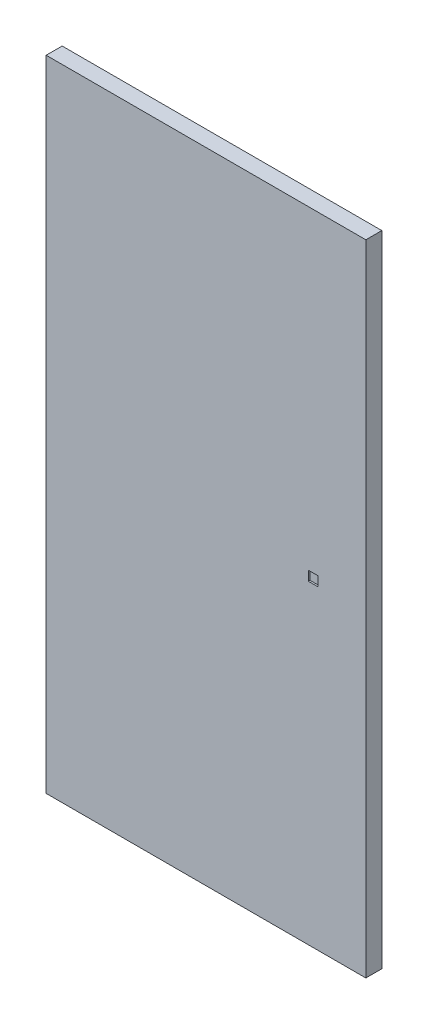
SolidWorks part; units mm, degrees
ref_plane "Front Plane" through (0, 0, 0) normal (0, 0, 1) x (1, 0, 0)
ref_plane "Top Plane" through (0, 0, 0) normal (0, 1, 0) x (1, 0, 0)
ref_plane "Right Plane" through (0, 0, 0) normal (1, 0, 0) x (0, 0, -1)
sketch "Sketch1" plane through (0, 0, 0) normal (0, 0, 1) x (1, 0, 0)
  line L1 (500, -1000) -> (-500, -1000)
  line L2 (500, -1000) -> (500, 1000)
  line L3 (500, 1000) -> (-500, 1000)
  line L4 (-500, -1000) -> (-500, 1000)
  line L5 (500, -1000) -> (-500, 1000) construction
  line L6 (500, 1000) -> (-500, -1000) construction
  point P0 (0, 0)
  dimension "D1" = 2000
  dimension "D2" = 1000
extrude "Boss-Extrude1" add sketch "Sketch1" along normal blind 50
sketch "Sketch2" plane through (0, 0, 50) normal (0, 0, 1) x (1, 0, 0)
  line L0 (500, 15) -> (-500, 15)
  line L1 (500, -1000) -> (500, 1000) construction
  line L2 (-500, 1000) -> (-500, -1000) construction
  line L3 (-934.7939, 0) -> (704.2445, 0) construction
  line L4 (-500, -15) -> (500, -15)
  line L5 (350, 1000) -> (350, -1000) construction
  line L6 (500, 1000) -> (-500, 1000) construction
  line L7 (-500, -1000) -> (500, -1000) construction
  line L9 (350, 15) -> (320, 15)
  line L10 (350, 15) -> (350, -15)
  line L11 (350, -15) -> (320, -15)
  line L12 (320, 15) -> (320, -15)
  line L13 (350, 15) -> (320, -15) construction
  line L14 (350, -15) -> (320, 15) construction
  point P21 (335, 0)
  dimension "D1" = 30
  dimension "D2" = 150
  dimension "D3" = 30
extrude "Cut-Extrude1" cut sketch "Sketch2" against normal blind 5 contours L0 L12 L4 L10
sketch "Sketch3" plane through (0, 0, 0) normal (0, 0, -1) x (-1, 0, 0)
  line L0 (-500, 15) -> (500, 15)
  line L1 (-500, -1000) -> (-500, 1000) construction
  line L2 (500, 1000) -> (500, -1000) construction
  line L3 (-500, -15) -> (500, -15)
  line L4 (-1196.52, 0) -> (973.7198, 0) construction
  line L5 (-350, 1000) -> (-350, -1000) construction
  line L6 (-500, 1000) -> (500, 1000) construction
  line L7 (500, -1000) -> (-500, -1000) construction
  line L9 (-350, 15) -> (-320, 15)
  line L10 (-350, 15) -> (-350, -15)
  line L11 (-350, -15) -> (-320, -15)
  line L12 (-320, 15) -> (-320, -15)
  line L13 (-350, 15) -> (-320, -15) construction
  line L14 (-350, -15) -> (-320, 15) construction
  point P21 (-335, 0)
  dimension "D1" = 30
  dimension "D2" = 150
  dimension "D3" = 30
extrude "Cut-Extrude2" cut sketch "Sketch3" against normal blind 5 contours L12 L0 L10 L3
